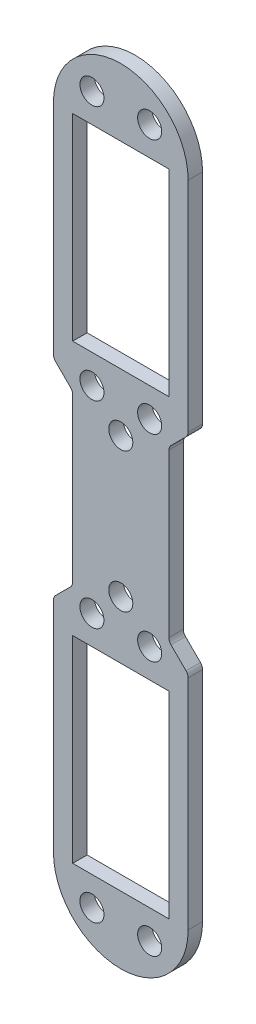
SolidWorks part; units mm, degrees
ref_plane "Front Plane" through (0, 0, 0) normal (0, 0, 1) x (1, 0, 0)
ref_plane "Top Plane" through (0, 0, 0) normal (0, 1, 0) x (1, 0, 0)
ref_plane "Right Plane" through (0, 0, 0) normal (1, 0, 0) x (0, 0, -1)
sketch "Sketch1" plane through (0, 0, 0) normal (0, 0, 1) x (1, 0, 0)
  line L0 (2.4, 9.401) -> (2.4, 13.5)
  line L1 (2.4, 13.5) -> (0.4, 13.5)
  line L2 (0, 0) -> (0, 4.6007)
  line L3 (0.4, 13.5) -> (0.4, 9.401)
  line L4 (2.8, 0) -> (2.8, 4.6008)
  line L5 (0.4, 9.401) -> (2.4, 9.401)
  line L6 (0.4, 5) -> (0.4, 8.5)
  line L7 (2.4, 5) -> (2.4, 8.5)
  line L8 (0.4, 0) -> (0.4, 13.5) construction
  line L9 (2.4, 0) -> (2.4, 13.5) construction
  line L10 (2.4, 8.5) -> (2.8, 8.9003)
  line L11 (0.4, 8.5) -> (0, 8.901)
  line L12 (0.4, 5) -> (0, 4.6007)
  line L13 (2.4, 5) -> (2.8, 4.6008)
  line L14 (0, 8.901) -> (0, 13.5)
  line L15 (0, 0) -> (0, 13.5) construction
  line L16 (0, 8.901) -> (0.4, 8.901) construction
  line L17 (0.4, 4.1007) -> (0.4, 0)
  line L18 (2.8, 8.9003) -> (2.8, 13.5)
  line L19 (2.8, 0) -> (2.8, 13.5) construction
  line L20 (0.4, 0) -> (2.4, 0)
  line L21 (2.4, 0) -> (2.4, 4.1007)
  line L22 (2.4, 4.1007) -> (0.4, 4.1007)
  line L23 (0, 4.6007) -> (0.4, 4.6007) construction
  arc A0 (0, 13.5) -> (2.8, 13.5) centre (1.4, 13.5) cw
  arc A1 (0, 0) -> (2.8, 0) centre (1.4, 0) ccw
  dimension "D1" = 2.8
  dimension "D2" = 13.5
  dimension "D3" = 0.5
  dimension "D4" = 0.5
  dimension "D5" = 0.4
  dimension "D6" = 0.4
extrude "Boss-Extrude1" add sketch "Sketch1" along normal blind 0.3
sketch "Sketch2" plane through (0, 0, 0.3) normal (0, 0, 1) x (1, 0, 0)
  line L0 (0.4, 6.75) -> (2.4, 6.75) construction
  line L1 (0.4, 8.5) -> (0.4, 5) construction
  line L2 (2.4, 5) -> (2.4, 8.5) construction
  line L13 (1.6, 8.8312) -> (2, 9.2315)
  line L14 (0.8, 9.2318) -> (1.2, 8.8308)
  line L15 (1.2, 4.6682) -> (0.8, 4.2689)
  line L16 (2, 4.269) -> (1.6, 4.6682)
  line L21 (2, 9.2315) -> (2, 13.5)
  line L22 (0.8, 13.5) -> (0.8, 9.2318)
  line L24 (1.2, 8.8308) -> (1.2, 4.6682)
  line L26 (0.8, 4.2689) -> (0.8, 0)
  line L27 (2, 0) -> (2, 4.269)
  line L29 (1.6, 4.6682) -> (1.6, 8.8312)
  arc A0 (1.8079, -0.4401) -> (1.8401, -0.4079) centre (1.4, 0) ccw
  circle A1 centre (0.8, 4.7007) radius 0.25
  circle A2 centre (2, 4.7007) radius 0.25
  circle A3 centre (1.4, 5.3007) radius 0.25
  circle A4 centre (2, 14.1) radius 0.25
  circle A5 centre (0.8, 14.1) radius 0.25
  circle A6 centre (2, 8.7993) radius 0.25
  circle A7 centre (0.8, 8.7993) radius 0.25
  circle A8 centre (1.4, 8.1993) radius 0.25
  circle A10 centre (0.8, -0.6) radius 0.25
  circle A11 centre (2, -0.6) radius 0.25
  arc A20 (2, 13.5) -> (0.8, 13.5) centre (1.4, 13.5) ccw
  arc A23 (0.8, 0) -> (2, 0) centre (1.4, 0) ccw
  arc A29 (0.9599, -0.4079) -> (0.9921, -0.4401) centre (1.4, 0) ccw
  dimension "D3" = 0.5
  dimension "D4" = 0.5
  dimension "D5" = 0.5
  dimension "D6" = 0.5
  dimension "D7" = 0.5
  dimension "D1" = 0.8
extrude "Cut-Extrude2" cut sketch "Sketch2" against normal blind 0.3 contours A29 A10 | A0 A11 | A2 | A3 | A1 | A7 | A8 | A6 | A5 | A4
fillet "Fillet10" radius 0.15 8 edges at (0, 4.6007, 0.15) (0.4, 5, 0.15) (0.4, 8.5, 0.15) (0, 8.901, 0.15) (2.4, 8.5, 0.15) (2.8, 8.9003, 0.15) (2.4, 5, 0.15) (2.8, 4.6008, 0.15)
